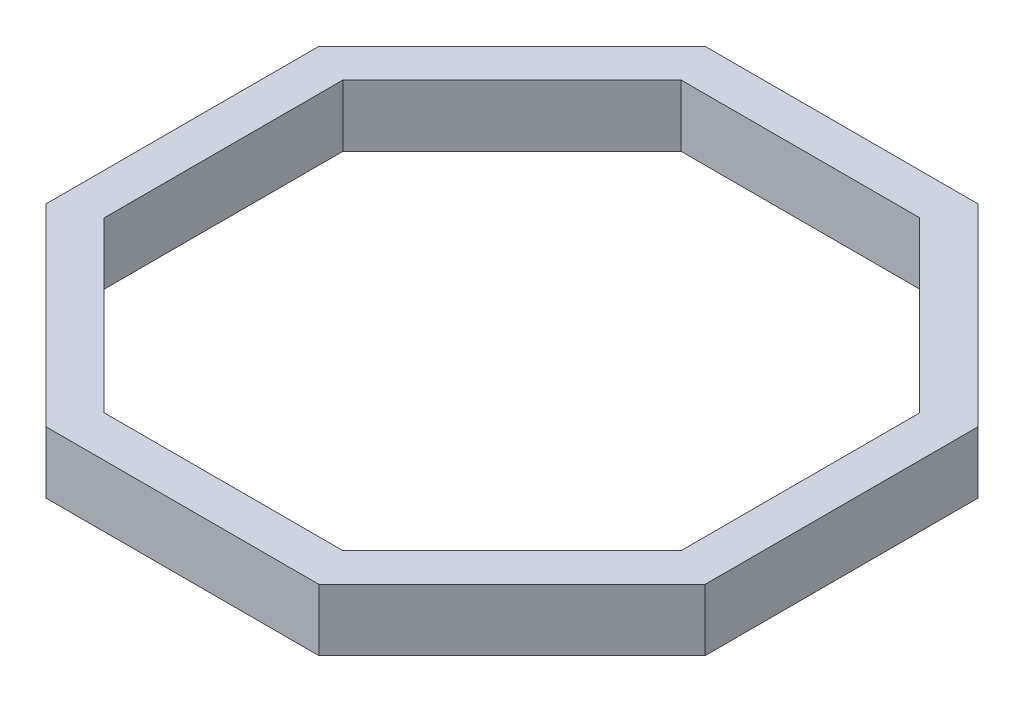
SolidWorks part; units mm, degrees
ref_plane "Plano frontal" through (0, 0, 0) normal (0, 0, 1) x (1, 0, 0)
ref_plane "Plano superior" through (0, 0, 0) normal (0, 1, 0) x (1, 0, 0)
ref_plane "Plano direito" through (0, 0, 0) normal (1, 0, 0) x (0, 0, -1)
sketch "Esboço1" plane through (0, 0, 0) normal (0, 1, 0) x (1, 0, 0)
  line L1 (160, 66.2742) -> (66.2742, 160)
  line L2 (66.2742, 160) -> (-66.2742, 160)
  line L3 (-66.2742, 160) -> (-160, 66.2742)
  line L4 (-160, 66.2742) -> (-160, -66.2742)
  line L5 (-160, -66.2742) -> (-66.2742, -160)
  line L6 (-66.2742, -160) -> (66.2742, -160)
  line L7 (66.2742, -160) -> (160, -66.2742)
  line L8 (160, -66.2742) -> (160, 66.2742)
  circle A0 centre (0, 0) radius 160 construction
extrude "Ressalto-extrusão1" add sketch "Esboço1" along normal blind 30
sketch "Esboço2" plane through (0, 30, 0) normal (0, 1, 0) x (1, 0, 0)
  line L1 (140, 57.9899) -> (57.9899, 140)
  line L2 (57.9899, 140) -> (-57.9899, 140)
  line L3 (-57.9899, 140) -> (-140, 57.9899)
  line L4 (-140, 57.9899) -> (-140, -57.9899)
  line L5 (-140, -57.9899) -> (-57.9899, -140)
  line L6 (-57.9899, -140) -> (57.9899, -140)
  line L7 (57.9899, -140) -> (140, -57.9899)
  line L8 (140, -57.9899) -> (140, 57.9899)
  circle A0 centre (0, 0) radius 140 construction
extrude "Corte-extrusão1" cut sketch "Esboço2" against normal blind 30
